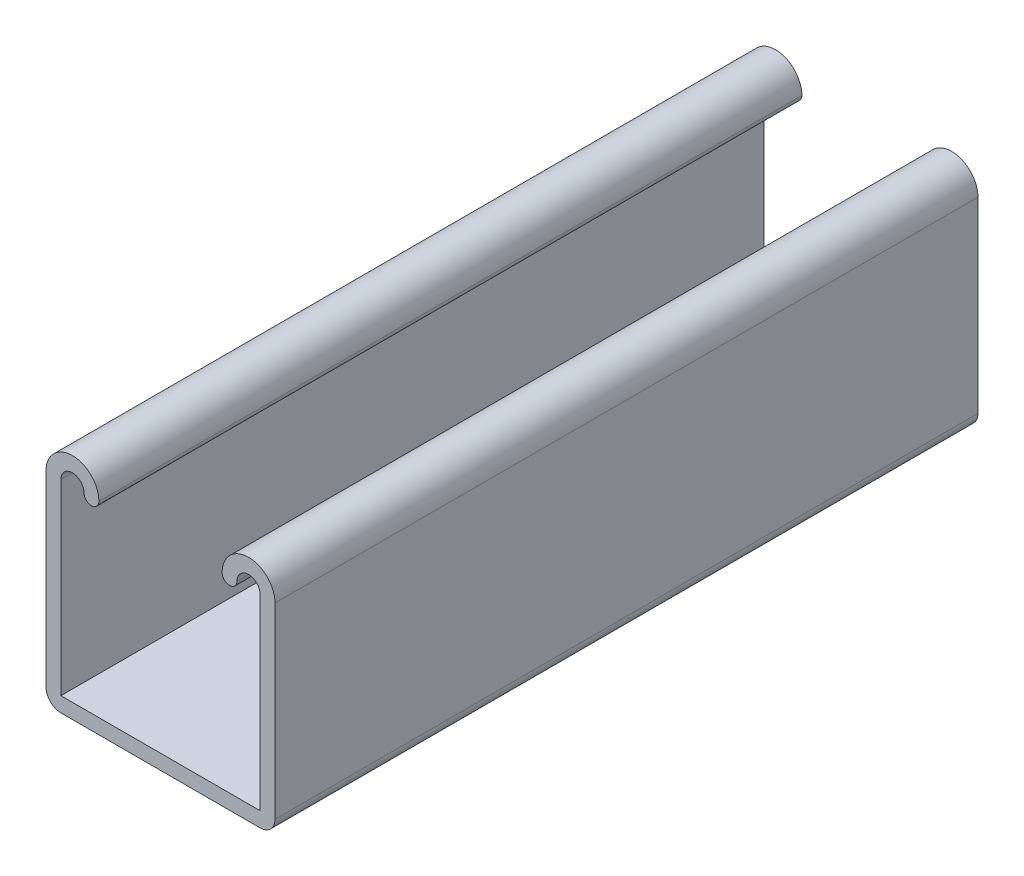
SolidWorks part; units mm, degrees
ref_plane "Front Plane" through (0, 0, 0) normal (0, 0, 1) x (1, 0, 0)
ref_plane "Top Plane" through (0, 0, 0) normal (0, 1, 0) x (1, 0, 0)
ref_plane "Right Plane" through (0, 0, 0) normal (1, 0, 0) x (0, 0, -1)
sketch "Sketch1" plane through (0, 0, 0) normal (0, 0, 1) x (1, 0, 0)
  line L0 (0, 0) -> (35.98, 0)
  line L1 (17.99, 2.6924) -> (17.99, -3.3917) construction
  line L2 (35.98, 2.6924) -> (0, 2.6924)
  line L3 (35.98, 19.6088) -> (0, 19.6088) construction
  line L4 (35.98, 2.6924) -> (35.98, 36.5252)
  line L5 (38.6724, 2.6924) -> (38.6724, 36.5252)
  line L6 (-2.6924, 2.6924) -> (-2.6924, 36.5252)
  line L7 (0, 2.6924) -> (0, 36.5252)
  line L8 (17.99, 19.6088) -> (17.99, 2.6924) construction
  arc A0 (35.98, 0) -> (38.6724, 2.6924) centre (35.98, 2.6924) ccw
  arc A1 (35.98, 36.5252) -> (31.8144, 36.5252) centre (33.8972, 36.5252) ccw
  arc A2 (38.6724, 36.5252) -> (29.122, 36.5252) centre (33.8972, 36.5252) ccw
  arc A3 (29.122, 36.5252) -> (31.8144, 36.5252) centre (30.4682, 36.5252) ccw
  arc A4 (6.858, 36.5252) -> (4.1656, 36.5252) centre (5.5118, 36.5252) cw
  arc A5 (-2.6924, 36.5252) -> (6.858, 36.5252) centre (2.0828, 36.5252) cw
  arc A6 (0, 36.5252) -> (4.1656, 36.5252) centre (2.0828, 36.5252) cw
  arc A7 (0, 0) -> (-2.6924, 2.6924) centre (0, 2.6924) cw
  point P25 (17.99, 19.6088)
extrude "Boss-Extrude1" add sketch "Sketch1" along normal blind 127
